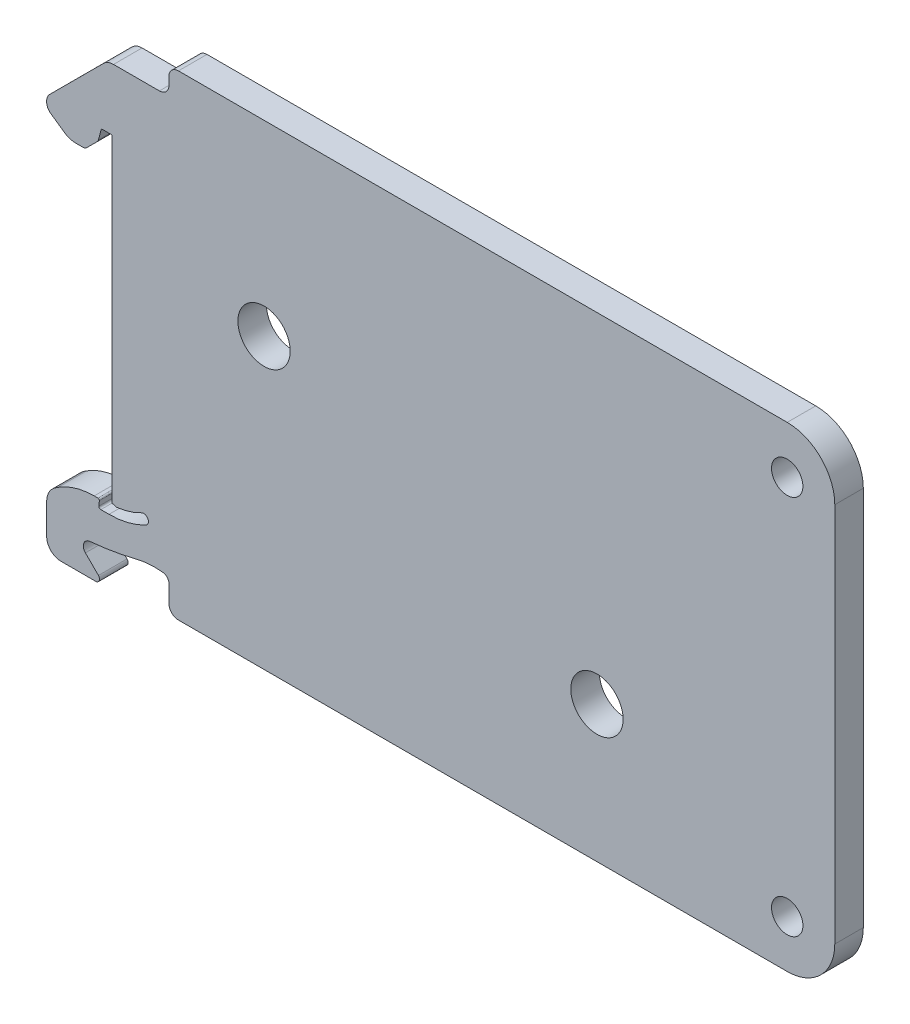
SolidWorks part; units mm, degrees
ref_plane "Front Plane" through (0, 0, 0) normal (0, 0, 1) x (1, 0, 0)
ref_plane "Top Plane" through (0, 0, 0) normal (0, 1, 0) x (1, 0, 0)
ref_plane "Right Plane" through (0, 0, 0) normal (1, 0, 0) x (0, 0, -1)
sketch "Sketch1" plane through (0, 0, 0) normal (0, 0, 1) x (1, 0, 0)
  line L0 (-27.5, 65.9546) -> (22.5, 65.9546) construction
  line L1 (-27.5, 40.9546) -> (-27.5, 43.7794)
  line L2 (-27.5, 90.9546) -> (-27.5, 88.1297)
  line L4 (-27.5, 40.9546) -> (22.5, 40.9546)
  line L5 (22.5, 40.9546) -> (22.5, 90.9546)
  line L6 (22.5, 90.9546) -> (-27.5, 90.9546)
  line L7 (22.5, 90.5) -> (22.5, 0) construction
  circle A0 centre (-17.5, 71.3) radius 2.75 construction
  circle A1 centre (17.5, 55.3) radius 2.75 construction
  circle A2 centre (-17.5, 71.3) radius 2.75
  circle A3 centre (17.5, 55.3) radius 2.75
  line B0 (-27.5, 43.7794) -> (-27.5, 88.1297)
  line B1 (-27.5, 88.1297) -> (-33.323, 88.1297)
  line B2 (-34.3832, 87.6909) -> (-40.0568, 82.0229)
  line B3 (-40.35, 81.3155) -> (-40.35, 81.1808)
  line B4 (-39.9236, 80.3616) -> (-38.4666, 79.3414)
  line B5 (-37.3194, 78.9797) -> (-36.5071, 78.9797)
  line B6 (-36.1536, 79.1261) -> (-35.0425, 80.2372)
  line B7 (-34.913, 80.4614) -> (-34.6, 81.6297)
  line B8 (-34.6, 81.6297) -> (-33.5, 81.6297)
  line B9 (-33.5, 81.6297) -> (-33.5, 48.0769)
  line B10 (-33.5, 48.0769) -> (-33.3, 48.0769)
  line B11 (-33.8, 46.9297) -> (-34.6605, 46.9297)
  line B12 (-34.8597, 47.1471) -> (-34.8143, 47.6666)
  line B13 (-34.9637, 47.8297) -> (-35.3565, 47.8297)
  line B14 (-40.35, 44.8393) -> (-40.35, 41.6297)
  line B15 (-38.85, 40.1297) -> (-35.1929, 40.1297)
  line B16 (-34.9101, 40.8125) -> (-36.2797, 42.1821)
  arc B17 (-33.323, 88.1297) -> (-34.3832, 87.6909) centre (-33.323, 86.6297) ccw
  arc B18 (-40.0568, 82.0229) -> (-40.35, 81.3155) centre (-39.35, 81.3155) ccw
  arc B19 (-40.35, 81.1808) -> (-39.9236, 80.3616) centre (-39.35, 81.1808) ccw
  arc B20 (-38.4666, 79.3414) -> (-37.3194, 78.9797) centre (-37.3194, 80.9797) ccw
  arc B21 (-36.5071, 78.9797) -> (-36.1536, 79.1261) centre (-36.5071, 79.4797) ccw
  arc B22 (-35.0425, 80.2372) -> (-34.913, 80.4614) centre (-35.396, 80.5908) ccw
  arc B23 (-33.3, 48.0769) -> (-32.9412, 47.9804) centre (-33, 48.4769) ccw
  arc B24 (-32.9412, 47.9804) -> (-30.384, 48.7783) centre (-33.8, 55.2297) ccw
  arc B25 (-29.916, 47.8945) -> (-30.384, 48.7783) centre (-30.15, 48.3364) ccw
  arc B26 (-33.8, 46.9297) -> (-29.916, 47.8945) centre (-33.8, 55.2297) ccw
  arc B27 (-34.8597, 47.1471) -> (-34.6605, 46.9297) centre (-34.6605, 47.1297) ccw
  arc B28 (-34.8143, 47.6666) -> (-34.9637, 47.8297) centre (-34.9637, 47.6797) ccw
  arc B29 (-35.3565, 47.8297) -> (-39.1546, 46.7097) centre (-35.3565, 40.8297) ccw
  arc B30 (-39.1546, 46.7097) -> (-39.51, 46.4685) centre (-34, 38.7297) ccw
  arc B31 (-39.51, 46.4685) -> (-40.35, 44.8393) centre (-38.35, 44.8393) ccw
  arc B32 (-40.35, 41.6297) -> (-38.85, 40.1297) centre (-38.85, 41.6297) ccw
  arc B33 (-35.1929, 40.1297) -> (-34.9101, 40.8125) centre (-35.1929, 40.5297) ccw
  arc B34 (-35.8167, 43.4594) -> (-36.2797, 42.1821) centre (-35.7493, 42.7125) ccw
  arc B35 (-35.8167, 43.4594) -> (-30.8576, 44.3024) centre (-38.7, 75.4297) ccw
  arc B36 (-28.115, 44.4742) -> (-30.8576, 44.3024) centre (-29.0253, 37.0297) ccw
  arc B37 (-27.5, 43.7794) -> (-28.115, 44.4742) centre (-28.2, 43.7794) ccw
  dimension "D1" = 50
  dimension "D2" = 50
sketch_block_instance "Block1-1"
sketch_block "Block1"
extrude "Boss-Extrude1" add sketch "Sketch1" along normal blind 3
sketch "Sketch2" plane through (0, 0, 3) normal (0, 0, 1) x (1, 0, 0)
  line L0 (-27.5, 90.9546) -> (42.5, 90.9546)
  line L2 (-27.5, 40.9546) -> (-27.5, 90.9546)
  line L9 (42.5, 90.9546) -> (42.5, 40.9546)
  line L10 (42.5, 40.9546) -> (-27.5, 40.9546)
  line L11 (22.5, 40.9546) -> (22.5, 90.9546) construction
  circle A1 centre (-17.5, 71.3) radius 2.75
  circle A2 centre (-17.5, 71.3) radius 2.75 construction
  circle A4 centre (17.5, 55.3) radius 2.75
  circle A5 centre (17.5, 55.3) radius 2.75 construction
  point P4 (0, 0)
  dimension "D1" = 50
  dimension "D2" = 20
extrude "Boss-Extrude2" add sketch "Sketch2" against normal up to surface (3 mm away) up to face at (-32.0975, 60.4081, 0)
fillet "Fillet1" radius 5 2 edges at (42.5, 40.9546, 1.5) (42.5, 90.9546, 1.5)
hole_wizard "Tap Drill for M4x0.7 Tap1" positions "Sketch3" profile "Sketch4" hole size "M4x0.7" standard "ANSI Metric"
sketch "Sketch3" plane through (0, 0, 3) normal (0, 0, 1) x (1, 0, 0)
  arc A0 (42.5, 85.9546) -> (37.5, 90.9546) centre (37.5, 85.9546) ccw construction
  arc A1 (37.5, 40.9546) -> (42.5, 45.9546) centre (37.5, 45.9546) ccw construction
  point P0 (37.5, 45.9546)
  point P2 (37.5, 85.9546)
sketch "Sketch4" plane through (37.5, 45.9546, 3) normal (1, 0, 0) x (0, -1, 0)
  line L0 (0, 0) -> (0, 5.9914)
  line L1 (0, 5.9914) -> (1.65, 5)
  line L2 (1.65, 5) -> (1.65, 0)
  line L5 (1.65, 0) -> (0, 0)
  line L10 (0, 5.9914) -> (-1.65, 5) construction
  line L11 (0, -6.35) -> (0, 107.95) construction
  dimension "Hole Dia." = 3.3
  dimension "Hole Depth" = 5
  dimension "Drill Angle" = 118
fillet "Fillet2" radius 1 3 edges at (-27.5, 90.9546, 1.5) (-27.5, 88.1297, 1.5) (-27.5, 40.9546, 1.5)
